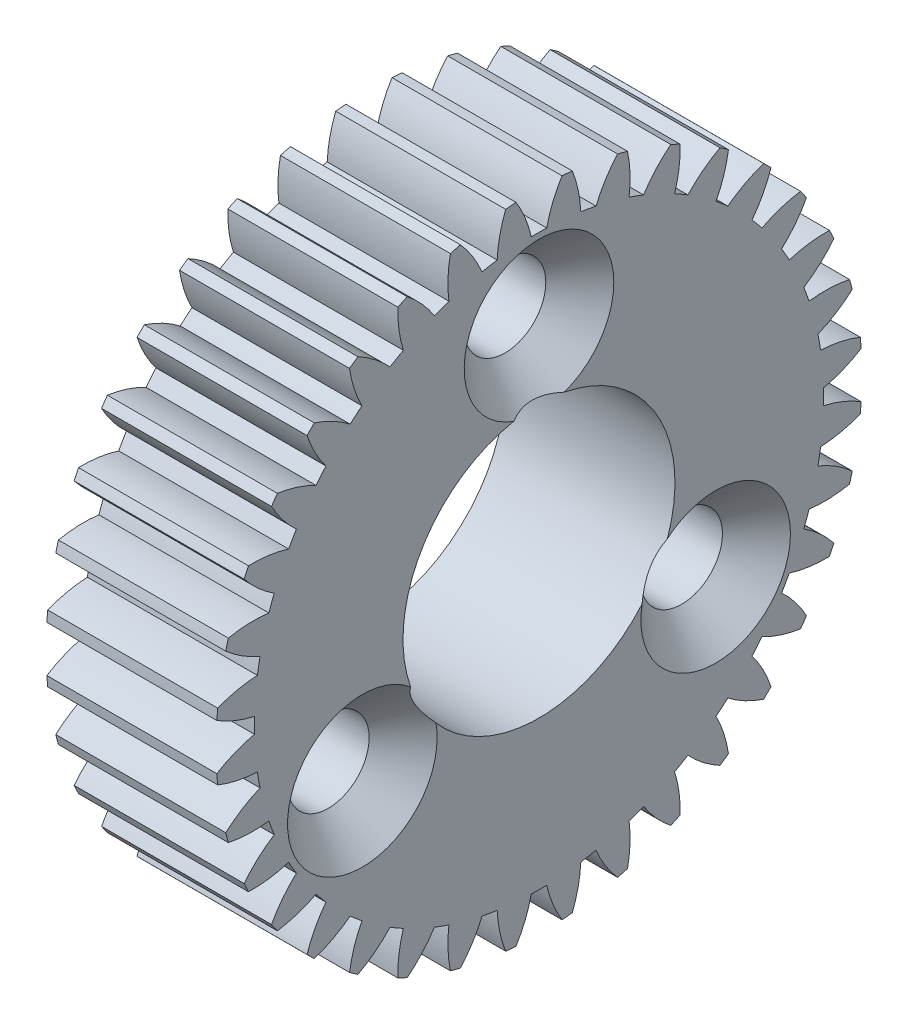
SolidWorks part; units mm, degrees
material "Náilon 101"
ref_plane "Plane1" through (0, 0, 0) normal (0, 0, 1) x (1, 0, 0)
ref_plane "Plane2" through (0, 0, 0) normal (0, 1, 0) x (1, 0, 0)
ref_plane "Plane3" through (0, 0, 0) normal (1, 0, 0) x (0, 0, -1)
sketch "HoldingSke" plane through (0, 0, 0) normal (0, 1, 0) x (1, 0, 0)
  line L0 (0, 0) -> (1.618, -1.1756)
  line L1 (-15, 0) -> (100, 0) construction
  line L2 (0, 0) -> (-2.1039, 2.3779)
  line L3 (0, 0) -> (-11.863, 4.5341)
  line L4 (0, 0) -> (6.9867, 5.0761)
  line L5 (0, 0) -> (-46.8476, -17.4728)
  line L6 (0, 0) -> (-2.4869, -1.6779)
  line L7 (-2.1039, 2.3779) -> (8.6586, 51.2059)
  line L8 (-76.2, 54.61) -> (-74.8, 54.61)
  line L9 (-71.009, 38.7566) -> (-53.1078, 45.2721)
  line L10 (-76.2, 71.12) -> (104.1128, 71.12)
  line L11 (0, 0) -> (-3, 0)
  line L12 (-76.2, 101.6) -> (-76.181, 101.6)
  line L13 (24.9733, 27.94) -> (52.9518, 28.4284)
  line L14 (24.9733, 27.94) -> (24.9743, 27.94)
  line L15 (24.9733, 27.94) -> (100.4006, 29.5858)
  line L16 (-63.627, -0.5) -> (-12.827, -0.5)
  circle A0 centre (0, 0) radius 4
  circle A1 centre (0, 0) radius 8.374
  circle A2 centre (0, 0) radius 37.5
  circle A3 centre (0, 0) radius 4
  dimension "MHD" = 16.748
  dimension "Hub_dia" = 75
  dimension "Bore" = 8
  dimension "MBD" = 8
  dimension "Num_teeth" = 36
  dimension "Pitch" = 2
  dimension "Overall_len" = 50
  dimension "Show_teeth" = 36
  dimension "Thickness" = 3
  dimension "OAL" = 50.0001
  dimension "T_dim" = 1.4
  dimension "Ap" = 20
  dimension "H" = 19.05
  dimension "Pitch_radius" = 180.3128
  dimension "Width" = 3
  dimension "Backlash" = 0.019
  dimension "Addendum_fac" = 1
  dimension "Dedendum_fac" = 1.25
  dimension "Clearance_fac" = 0.25
  dimension "Dedendum_add" = 0.001
  dimension "Module" = 0.5
sketch "BasProSke" plane through (0, 0, 0) normal (0, 1, 0) x (1, 0, 0)
  line L0 (-10, 0) -> (60, 0) construction
  line L1 (0, 0) -> (0, 9.5)
  line L2 (0, 0) -> (5, 0)
  line L3 (5, 0) -> (5, 9.5)
  line L4 (5, 9.5) -> (0, 9.5)
  dimension "Thickness" = 5
  dimension "Diameter" = 19
revolve "Base-Revolve" add sketch "BasProSke" angle 360 about L0
sketch "TooCutSke" plane through (0, 0, 0) normal (1, 0, 0) x (0, 0, -1)
  line L1 (0, 0) -> (0, 107) construction
  line L2 (0, 0) -> (-0.4258, 8.9899) construction
  line L3 (0, 0) -> (-1.5676, 17.9172) construction
  line L4 (-0.4258, 8.9899) -> (-0.7838, 8.9586) construction
  arc A0 (0.2272, 8.3709) -> (-0.2272, 8.3709) centre (0, 0) ccw
  arc A1 (0.6921, 9.5002) -> (-0.6921, 9.5002) centre (0, 0) ccw
  circle A2 centre (0, 0) radius 9 construction
  circle A3 centre (0, 0) radius 8.4572 construction
  arc A4 (-0.2272, 8.3709) -> (-0.6921, 9.5002) centre (-3.7404, 7.5851) ccw
  arc A5 (0.6921, 9.5002) -> (0.2272, 8.3709) centre (3.7404, 7.5851) ccw
  dimension "Root_dia" = 16.748
  dimension "Overcut_dia" = 19.0508
  dimension "Pitch_dia" = 18
  dimension "Base_dia" = 16.9145
  dimension "Flank_rad" = 3.6
  dimension "Half_ang" = 5
  dimension "Half_CT" = 0.3593
extrude "ToothCut" cut sketch "TooCutSke" along normal through all
fillet "Breaks" [suppressed] radius 0.01
fillet "RootFillets" [suppressed] radius 0.126
pattern_circular "TeethCuts" count 36 every 10 about axis through (-10, 0, 0) along (1, 0, 0) of "ToothCut", "RootFillets", "Breaks"
sketch "HubNeaOneSke" plane through (0, 0, 0) normal (-1, 0, 0) x (0, 0, 1)
  circle A0 centre (0, 0) radius 8.374
  dimension "Diameter" = 16.748
extrude "HubNearOne" [suppressed] add sketch "HubNeaOneSke" along normal blind 45.0001
sketch "HubNeaBotSke" plane through (0, 0, 0) normal (-1, 0, 0) x (0, 0, 1)
  circle A0 centre (0, 0) radius 8.374
  dimension "Diameter" = 16.748
extrude "HubNearBoth" [suppressed] add sketch "HubNeaBotSke" along normal blind 22.5
ref_plane "FarPln" through (5, 0, 0) normal (1, 0, 0) x (0, 0, -1)
sketch "HubFarSke" plane through (5, 0, 0) normal (1, 0, 0) x (0, 0, -1)
  circle A0 centre (0, 0) radius 8.374
  dimension "Diameter" = 16.748
extrude "HubFar" [suppressed] add sketch "HubFarSke" along normal blind 22.5
sketch "BorSke" plane through (0, 0, 0) normal (1, 0, 0) x (0, 0, -1)
  circle A0 centre (0, 0) radius 4
  dimension "Diameter" = 8
extrude "Bore" cut sketch "BorSke" along normal mid plane 100.0001
sketch "KeySke" plane through (0, 0, 0) normal (1, 0, 0) x (0, 0, -1)
  line L0 (-1.5, 0) -> (-1.5, 5.4)
  line L1 (-1.5, 5.4) -> (1.5, 5.4)
  line L2 (1.5, 5.4) -> (1.5, 0)
  line L3 (0, 0) -> (0, 34) construction
  line L4 (-1.5, 0) -> (1.5, 0)
  dimension "Width" = 3
  dimension "Offset" = 5.4
extrude "Keyway" [suppressed] cut sketch "KeySke" along normal mid plane 100.0001
pattern_circular "Keyway2" [suppressed] count 2 every 90 about axis through (-10, 0, 0) along (1, 0, 0)
sketch "Esboço1" plane through (5, 0, 0) normal (1, 0, 0) x (0, 0, -1)
  circle A0 centre (0, 0) radius 6 construction
  point P3 (0, 6)
  dimension "D1" = 12
sketch "Esboço3" plane through (5, 0, 0) normal (1, 0, 0) x (0, 0, -1)
  line L0 (0, 0) -> (4, 0) construction
  line L1 (0, 0) -> (-4, 0) construction
  circle A0 centre (0, 0) radius 4 construction
  circle A1 centre (0, 0) radius 4 construction
hole_wizard "Escareado para parafuso com cabeça escareada elevada de M21" positions "3DSketch1" profile "Esboço4" countersink size "M2" standard "ISO"
sketch3d "3DSketch1"
  point P0 (5, 6, 0)
sketch "Esboço4" plane through (5, 6, 0) normal (0, 1, 0) x (0, 0, -1)
  line L0 (0, 0) -> (0, 6.721)
  line L1 (0, 6.721) -> (1.2, 6)
  line L2 (1.2, 6) -> (1.2, 1)
  line L3 (1.2, 1) -> (2.2, 0)
  line L5 (2.2, 0) -> (0, 0)
  line L6 (-1.2, 1) -> (-2.2, 0) construction
  line L10 (0, 6.721) -> (-1.2, 6) construction
  line L11 (0, -6.35) -> (0, 107.95) construction
  dimension "Hole Dia." = 2.4
  dimension "Hole Depth" = 6
  dimension "Near C'Sink Dia." = 4.4
  dimension "Near C'Sink Angle" = 90
  dimension "Drill Angle" = 118
pattern_circular "PadrãoCircular1" count 3 over 360 about axis through (0, 0, 0) along (1, 0, 0) of "Escareado para parafuso com cabeça escareada elevada de M21"
equation "' \"Module@HoldingSke\" = 6.35"
equation "' \"Num_teeth@HoldingSke\" = 12"
equation "' \"Ap@HoldingSke\" =  20"
equation "' \"Ap@HoldingSke\" = 20"
equation "' \"Width@HoldingSke\" = 0.5 * 25.4"
equation "' \"Hub_dia@HoldingSke\"= 1 * 25.4"
equation "' \"Hub_dia@HoldingSke\" = 1 * 25.4"
equation "' \"Overall_len@HoldingSke\" = 1.0 * 25.4"
equation "' \"Bore@HoldingSke\" = 0.75 * 25.4"
equation "' \"T_dim@HoldingSke\" = 0.1 * 25.4"
equation "' \"Width@KeySke\" = 0.25 * 25.4"
equation "' \"Show_teeth@HoldingSke\" = 13"
equation "' \"Backlash@HoldingSke\" = 0.009 * 25.4"
equation "' \"Addendum_fac@HoldingSke\" = 1.0"
equation "' \"Dedendum_fac@HoldingSke\" = 1.25"
equation "' \"Dedendum_add@HoldingSke\" = 0.00005 * 25.4"
equation "' \"Clearance_fac@HoldingSke\" = 0.25"
equation "\"Pitch@HoldingSke\" = 1 / \"Module@HoldingSke\""
equation "\"Overcut_dia@TooCutSke\" = (\"Num_teeth@HoldingSke\" + 2 * \"Addendum_fac@HoldingSke\") / \"Pitch@HoldingSke\" + 0.002 * 25.4"
equation "\"Pitch_dia@TooCutSke\" = \"Num_teeth@HoldingSke\" / \"Pitch@HoldingSke\""
equation "\"Base_dia@TooCutSke\" = \"Num_teeth@HoldingSke\" / \"Pitch@HoldingSke\" * cos((\"Ap@HoldingSke\"  * 3.14159265 / 180))"
equation "\"Root_dia@TooCutSke\" = (\"Num_teeth@HoldingSke\" + 2) / \"Pitch@HoldingSke\" - 2 * (\"Addendum_fac@HoldingSke\" + \"Dedendum_fac@HoldingSke\") / \"Pitch@HoldingSke\" - \"Dedendum_add@HoldingSke\" * 2"
equation "\"Half_ang@TooCutSke\" = 180 / \"Num_teeth@HoldingSke\""
equation "\"Half_CT@TooCutSke\" = \"Num_teeth@HoldingSke\" / \"Pitch@HoldingSke\" * sin((3.14159265 / 2 / \"Num_teeth@HoldingSke\")) / 2 - 7 * \"Backlash@HoldingSke\" / 4"
equation "\"Flank_rad@TooCutSke\" = \"Num_teeth@HoldingSke\" / \"Pitch@HoldingSke\" / 5"
equation "\"Radius@RootFillets\" = \"Clearance_fac@HoldingSke\" / \"Pitch@HoldingSke\" + \"Dedendum_add@HoldingSke\""
equation "\"Break_rad@Breaks\" = 0.02 / \"Pitch@HoldingSke\""
equation "\"Thickness@HoldingSke\" = \"Width@HoldingSke\""
equation "\"OAL@HoldingSke\" = \"Thickness@HoldingSke\""
equation "\"MHD@HoldingSke\" = (\"Num_teeth@HoldingSke\" + 2) / \"Pitch@HoldingSke\" - 2 * (\"Addendum_fac@HoldingSke\" + \"Dedendum_fac@HoldingSke\")  / \"Pitch@HoldingSke\" - \"Dedendum_add@HoldingSke\" * 2"
equation "\"MBD@HoldingSke\" = (\"Num_teeth@HoldingSke\" + 2) / \"Pitch@HoldingSke\" - 2 * (\"Addendum_fac@HoldingSke\" + \"Dedendum_fac@HoldingSke\")  / \"Pitch@HoldingSke\" - \"Dedendum_add@HoldingSke\" * 2 - 0.002 * 25.4"
equation "\"MHD@HoldingSke\" = ((sgn( \"MHD@HoldingSke\" - \"Hub_dia@HoldingSke\" )-1)*( \"MHD@HoldingSke\" - \"Hub_dia@HoldingSke\" ))/-2+ \"Hub_dia@HoldingSke\""
equation "\"MBD@HoldingSke\" = ((sgn( \"MBD@HoldingSke\" - \"Bore@HoldingSke\" )-1)*( \"MBD@HoldingSke\" - \"Bore@HoldingSke\" ))/-2+ \"Bore@HoldingSke\""
equation "\"OAL@HoldingSke\" = ((sgn( \"OAL@HoldingSke\" - \"Overall_len@HoldingSke\" )+1)*( \"OAL@HoldingSke\" - \"Overall_len@HoldingSke\" ))/2 + \"Overall_len@HoldingSke\" + 0.000002 * 25.4"
equation "\"Num_teeth@TeethCuts\" = int( \"Show_teeth@HoldingSke\" ) + 1"
equation "\"Num_teeth@TeethCuts\" = ((sgn( \"Num_teeth@TeethCuts\" - \"Num_teeth@HoldingSke\" )-1)*( \"Num_teeth@TeethCuts\" - \"Num_teeth@HoldingSke\" ))/-2+ \"Num_teeth@HoldingSke\""
equation "\"Num_teeth@TeethCuts\" = ((sgn( \"Num_teeth@TeethCuts\" - 2.0)+1)*( \"Num_teeth@TeethCuts\" - 2.0))/2 +2.0"
equation "\"Angle@TeethCuts\" = 360.0 / \"Num_teeth@HoldingSke\""
equation "\"Diameter@BasProSke\" = (\"Num_teeth@HoldingSke\" + 2 * \"Addendum_fac@HoldingSke\") / \"Pitch@HoldingSke\""
equation "' \"Fillet_rad@BasProSke\" =  \"Thickness@HoldingSke\" * 0.05"
equation "' \"Fillet_rad@BasProSke\" = \"Thickness@HoldingSke\" * 0.05"
equation "\"MHD@HoldingSke\" = ((sgn( \"MHD@HoldingSke\" - \"Root_dia@TooCutSke\" )-1)*( \"MHD@HoldingSke\" - \"Root_dia@TooCutSke\" ))/-2+ \"Root_dia@TooCutSke\""
equation "\"Diameter@HubNeaOneSke\" = \"MHD@HoldingSke\""
equation "\"Length@HubNearOne\" = \"OAL@HoldingSke\" - \"Thickness@BasProSke\""
equation "\"Diameter@HubNeaBotSke\" = \"MHD@HoldingSke\""
equation "\"Length@HubNearBoth\" = ( \"OAL@HoldingSke\" - \"Thickness@BasProSke\" ) / 2.0"
equation "\"Thickness@FarPln\" = \"Thickness@BasProSke\""
equation "\"Diameter@HubFarSke\" = \"MHD@HoldingSke\""
equation "\"Length@HubFar\" = ( \"OAL@HoldingSke\" - \"Thickness@BasProSke\" ) / 2.0"
equation "\"Diameter@BorSke\" = \"MBD@HoldingSke\""
equation "\"D1@Bore\" = \"OAL@HoldingSke\" * 2.0"
equation "\"D1@Keyway\" = \"OAL@HoldingSke\" * 2.0"
equation "\"Offset@KeySke\" = \"T_dim@HoldingSke\" + \"MBD@HoldingSke\" / 2.0"
